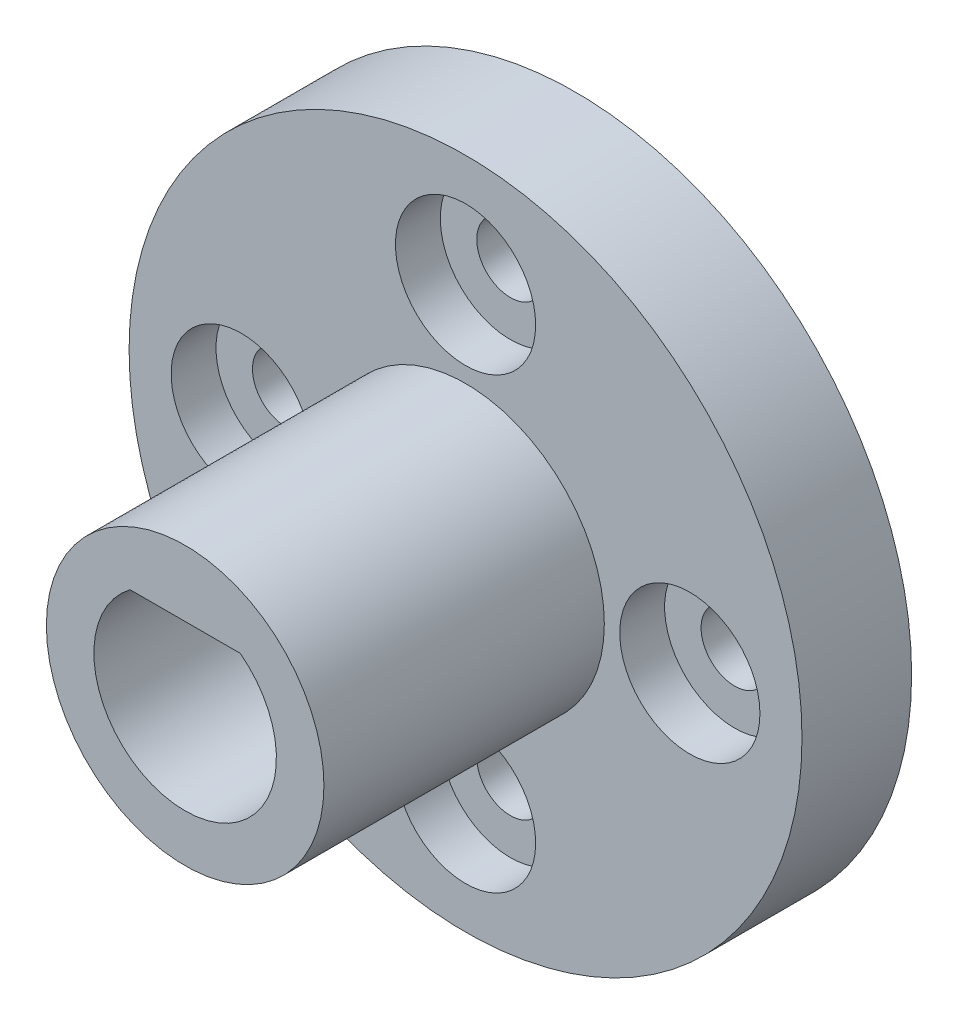
SolidWorks part; units mm, degrees
ref_plane "Plan de face" through (0, 0, 0) normal (0, 0, 1) x (1, 0, 0)
ref_plane "Plan de dessus" through (0, 0, 0) normal (0, 1, 0) x (1, 0, 0)
ref_plane "Plan de droite" through (0, 0, 0) normal (1, 0, 0) x (0, 0, -1)
sketch "Esquisse1" plane through (0, 0, 0) normal (0, 0, 1) x (1, 0, 0)
  circle A0 centre (0, 0) radius 12
  dimension "D1" = 24
extrude "Boss.-Extru.1" add sketch "Esquisse1" along normal blind 3.91
sketch "Esquisse6" plane through (0, 0, 0) normal (0, 0, -1) x (-1, 0, 0)
  circle A0 centre (0, 0) radius 4.15
  dimension "D1" = 8.3
extrude "Enlèv. mat.-Extru.2" cut sketch "Esquisse6" against normal blind 1.91
sketch "Esquisse7" plane through (0, 0, 3.91) normal (0, 0, 1) x (1, 0, 0)
  line L0 (1.9649, 2.595) -> (-1.9649, 2.595)
  line L1 (-5.4714, -3.255) -> (6.192, -3.255) construction
  arc A0 (-1.9649, 2.595) -> (1.9649, 2.595) centre (0, 0) ccw
  circle A1 centre (0, 0) radius 4.95
  dimension "D1" = 6.51
  dimension "D3" = 9.9
  dimension "D2" = 5.85
extrude "Boss.-Extru.2" add sketch "Esquisse7" along normal blind 10 contours A1 L1 A0 L0 | L1 A1
hole_wizard "Chambrage pour vis à tête ronde bombée M21" positions "Esquisse10" profile "Esquisse11" counterbore size "M2" standard "Ansi Metric" end condition through all
sketch "Esquisse10" plane through (0, 0, 3.91) normal (0, 0, 1) x (1, 0, 0)
  point P0 (0, 8)
  dimension "D1" = 8
sketch "Esquisse11" plane through (0, 8, 3.91) normal (1, 0, 0) x (0, -1, 0)
  line L0 (0, 0) -> (0, 3.91)
  line L1 (0, 3.91) -> (1.2, 3.91)
  line L3 (1.2, 3.91) -> (1.2, 1.6)
  line L4 (1.2, 1.6) -> (2.5, 1.6)
  line L5 (2.5, 1.6) -> (2.5, 0)
  line L7 (2.5, 0) -> (0, 0)
  line L11 (0, -6.35) -> (0, 107.95) construction
  dimension "Diamètre du perçage jusqu'au prochain" = 2.4
  dimension "Profondeur du perçage jusqu'au prochain" = 3.91
  dimension "Diamètre du chambrage" = 5
  dimension "Profondeur du chambrage" = 1.6
pattern_circular "Répétition circulaire2" count 4 every 90 about axis through (0, 0, 0) along (0, 0, 1) of "Chambrage pour vis à tête ronde bombée M21"
